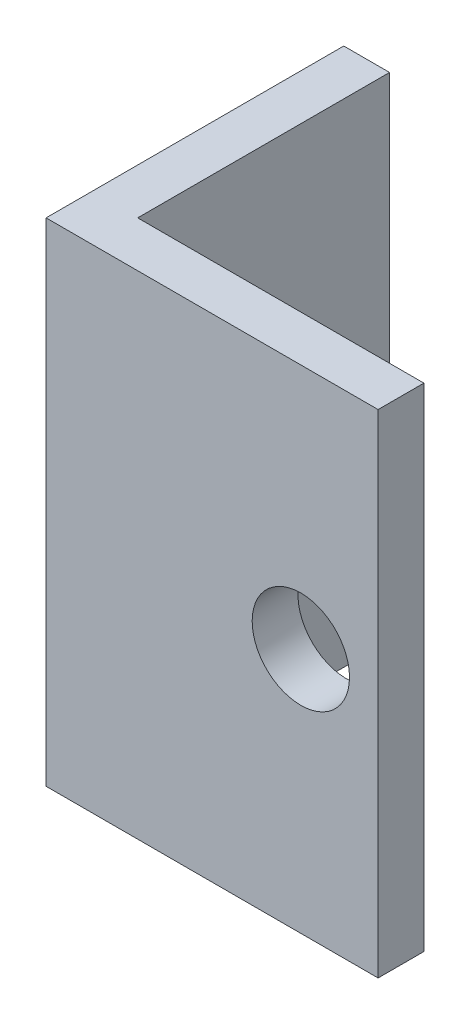
SolidWorks part; units mm, degrees
ref_plane "Alzado" through (0, 0, 0) normal (0, 0, 1) x (1, 0, 0)
ref_plane "Planta" through (0, 0, 0) normal (0, 1, 0) x (1, 0, 0)
ref_plane "Vista lateral" through (0, 0, 0) normal (1, 0, 0) x (0, 0, -1)
sketch "Croquis1" plane through (0, 0, 0) normal (0, 1, 0) x (1, 0, 0)
  line L0 (0, 0) -> (25, 0)
  line L1 (25, 0) -> (25, -3)
  line L2 (25, -3) -> (0, -3)
  line L3 (0, -3) -> (0, 0)
extrude "Saliente-Extruir1" add sketch "Croquis1" along normal blind 195
sketch "Croquis2" plane through (0, 0, 3) normal (0, 0, 1) x (1, 0, 0)
  line L0 (0, 195) -> (0, 0) construction
  line L1 (0, 0) -> (25, 0) construction
  line L2 (0, 195) -> (25, 195) construction
  circle A0 centre (18.25, 180) radius 4.25
  circle A1 centre (18.25, 97.5) radius 4.25
  circle A2 centre (18.25, 15) radius 4.25
  dimension "D1" = 18.25
  dimension "D2" = 15
  dimension "D3" = 97.5
  dimension "D4" = 15
extrude "Cortar-Extruir1" cut sketch "Croquis2" against normal blind 195
sketch "Croquis3" plane through (0, 195, 0) normal (0, 1, 0) x (1, 0, 0)
  line L1 (0, -3) -> (-4, -3)
  line L2 (0, -3) -> (0, 22)
  line L3 (0, 22) -> (-4, 22)
  line L4 (-4, -3) -> (-4, 22)
  dimension "D1" = 4
extrude "Saliente-Extruir2" add sketch "Croquis3" against normal blind 195
sketch "Croquis4" plane through (0, 0, 3) normal (0, 0, 1) x (1, 0, 0)
  line L1 (25, 195) -> (-4, 195)
  line L2 (25, 195) -> (25, 0)
  line L3 (25, 0) -> (-4, 0)
  line L4 (-4, 195) -> (-4, 0)
  circle A0 centre (18.25, 15) radius 4.25
  circle A1 centre (18.25, 97.5) radius 4.25
  circle A2 centre (18.25, 180) radius 4.25
extrude "Saliente-Extruir3" add sketch "Croquis4" along normal blind 1
sketch "Croquis5" plane through (0, 0, 4) normal (0, 0, 1) x (1, 0, 0)
  line L0 (25, 195) -> (-4, 195) construction
  line L1 (25, 0) -> (-124.8114, 0)
  line L2 (25, 0) -> (25, 152)
  line L3 (25, 152) -> (-124.8114, 152)
  line L4 (-124.8114, 0) -> (-124.8114, 152)
  dimension "D1" = 43
extrude "Cortar-Extruir4" cut sketch "Croquis5" against normal blind 40
sketch "Croquis6" plane through (0, 0, 4) normal (0, 0, 1) x (1, 0, 0)
  line L0 (25, 152) -> (25, 195) construction
  circle A0 centre (18.25, 173.5) radius 4.25
  point P4 (25, 173.5)
  dimension "D1" = 0
extrude "Cortar-Extruir5" cut sketch "Croquis6" against normal blind 40
sketch "Croquis7" plane through (0, 0, 4) normal (0, 0, 1) x (1, 0, 0)
  circle A0 centre (18.25, 180) radius 4.25
  circle A1 centre (18.25, 173.5) radius 4.25
  arc M5 (15.5114, 176.75) -> (20.9886, 176.75) centre (18.25, 180) cw
extrude "Saliente-Extruir4" add sketch "Croquis7" against normal blind 4 contours A1 M5
